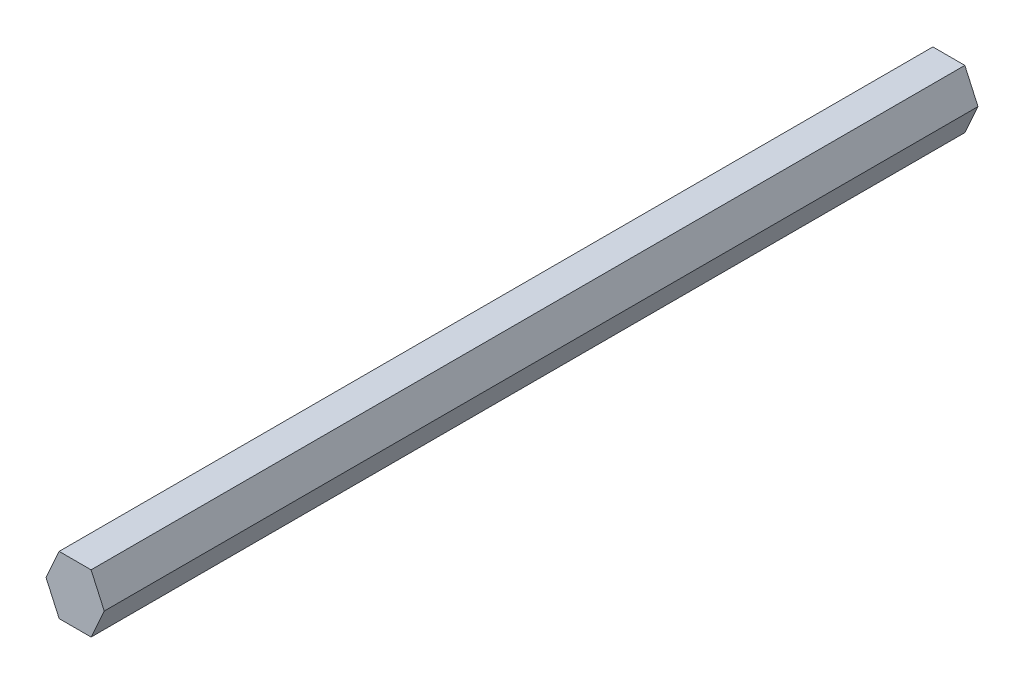
SolidWorks part; units mm, degrees
ref_plane "Front Plane" through (0, 0, 0) normal (0, 0, 1) x (1, 0, 0)
ref_plane "Top Plane" through (0, 0, 0) normal (0, 1, 0) x (1, 0, 0)
ref_plane "Right Plane" through (0, 0, 0) normal (1, 0, 0) x (0, 0, -1)
sketch "Sketch1" plane through (0, 0, 0) normal (0, 0, 1) x (1, 0, 0)
  line L6 (4.3283, 2.194) -> (3.1989, 4.6936)
  line L7 (3.1989, 4.6936) -> (0.4559, 4.6936)
  line L8 (0.4559, 4.6936) -> (-0.6717, 2.1932)
  line L9 (-0.6717, 2.1932) -> (0.4577, -0.3064)
  line L10 (0.4577, -0.3064) -> (3.2007, -0.3064)
  line L11 (3.2007, -0.3064) -> (4.3283, 2.194)
  point P4 (0.1109, -0.0511)
  dimension "D1" = 5
  dimension "D2" = 5
extrude "Boss-Extrude1" add sketch "Sketch1" along normal blind 75
